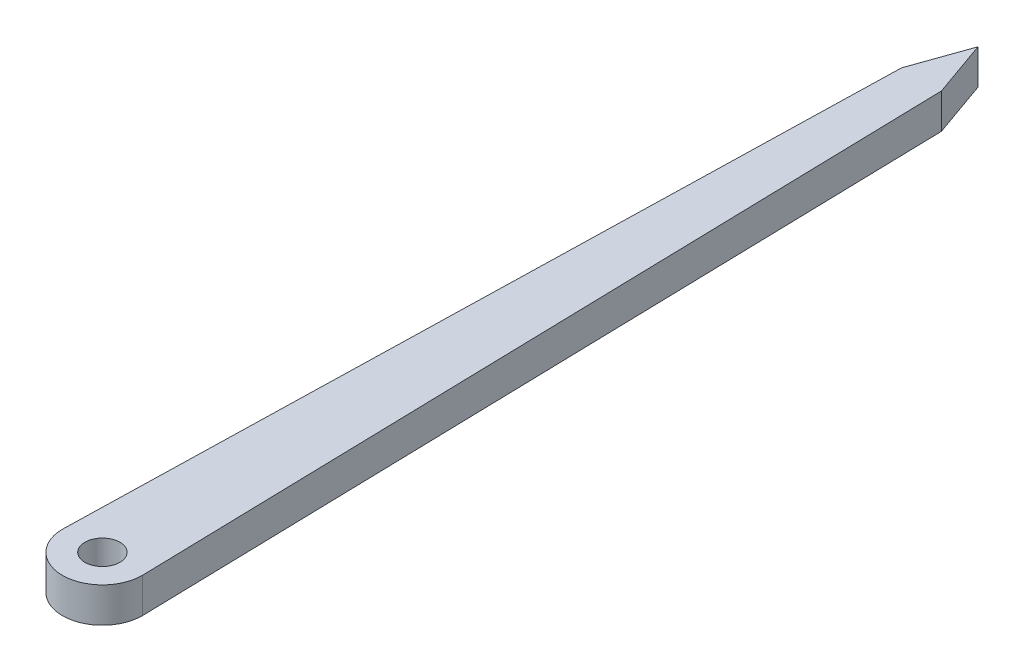
SolidWorks part; units mm, degrees
ref_plane "Přední rovina" through (0, 0, 0) normal (0, 0, 1) x (1, 0, 0)
ref_plane "Horní rovina" through (0, 0, 0) normal (0, 1, 0) x (1, 0, 0)
ref_plane "Pravá rovina" through (0, 0, 0) normal (1, 0, 0) x (0, 0, -1)
sketch "Skica1" plane through (0, 0, 0) normal (0, 1, 0) x (1, 0, 0)
  line L0 (-4, 0) -> (-2, 82)
  line L1 (-2, 82) -> (0, 87.6569)
  line L2 (0, 87.6569) -> (2, 82)
  line L3 (2, 82) -> (4, 0)
  circle A4 centre (0, 0) radius 4
  circle A5 centre (0, 0) radius 1.75
  point P2 (0, 0)
  dimension "D1" = 8
  dimension "D2" = 3.5
  dimension "D7" = 4
  dimension "D8" = 82
  dimension "D3" = 0
  dimension "D4" = 6
  dimension "D5" = 6
  dimension "D6" = 82
extrude "Přidat vysunutím1" add sketch "Skica1" along normal blind 3.5 contours A4 L3 L2 L1 L0 | L3 A4 L0 A5
